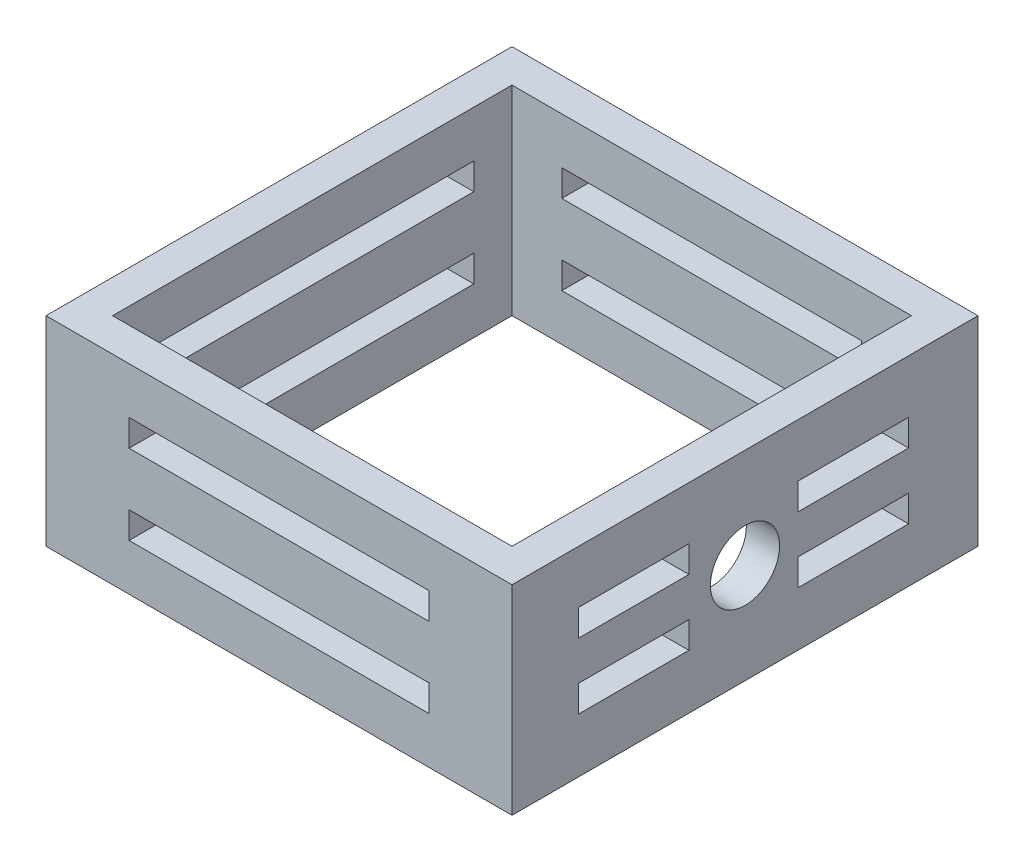
SolidWorks part; units mm, degrees
ref_plane "Front Plane" through (0, 0, 0) normal (0, 0, 1) x (1, 0, 0)
ref_plane "Top Plane" through (0, 0, 0) normal (0, 1, 0) x (1, 0, 0)
ref_plane "Right Plane" through (0, 0, 0) normal (1, 0, 0) x (0, 0, -1)
sketch "Sketch2" plane through (0, 0, 0) normal (0, 1, 0) x (1, 0, 0)
  line L1 (-17.5, 17.5) -> (17.5, 17.5)
  line L2 (-17.5, 17.5) -> (-17.5, -17.5)
  line L3 (-17.5, -17.5) -> (17.5, -17.5)
  line L4 (17.5, 17.5) -> (17.5, -17.5)
  line L5 (-17.5, 17.5) -> (17.5, -17.5) construction
  line L6 (-17.5, -17.5) -> (17.5, 17.5) construction
  point P0 (0, 0)
  dimension "D1" = 35
  dimension "D2" = 35
extrude "Boss-Extrude1" add sketch "Sketch2" along normal blind 10 contours L2 L1 L4 L3
sketch "Sketch3" plane through (0, 10, 0) normal (0, 1, 0) x (1, 0, 0)
  line L1 (-17.5, 17.5) -> (17.5, 17.5)
  line L2 (-17.5, 17.5) -> (-17.5, -17.5)
  line L3 (-17.5, -17.5) -> (17.5, -17.5)
  line L4 (17.5, 17.5) -> (17.5, -17.5)
  line L5 (-17.5, 17.5) -> (17.5, -17.5) construction
  line L6 (-17.5, -17.5) -> (17.5, 17.5) construction
  line L7 (-15, 15) -> (15, 15)
  line L8 (-15, 15) -> (-15, -15)
  line L9 (-15, -15) -> (15, -15)
  line L10 (15, 15) -> (15, -15)
  line L11 (-15, 15) -> (15, -15) construction
  line L12 (-15, -15) -> (15, 15) construction
  point P0 (0, 0)
  point P7 (0, 0)
  dimension "D1" = 30
extrude "Boss-Extrude2" add sketch "Sketch3" along normal blind 15 separate body
sketch "Sketch4" plane through (0, 25, 0) normal (0, 1, 0) x (1, 0, 0)
  line L1 (-17.5, 17.5) -> (17.5, 17.5)
  line L2 (-17.5, 17.5) -> (-17.5, -17.5)
  line L3 (-17.5, -17.5) -> (17.5, -17.5)
  line L4 (17.5, 17.5) -> (17.5, -17.5)
  line L5 (-17.5, 17.5) -> (17.5, -17.5) construction
  line L6 (-17.5, -17.5) -> (17.5, 17.5) construction
  point P0 (0, 0)
extrude "Boss-Extrude3" add sketch "Sketch4" along normal blind 15 separate body
sketch "Sketch5" plane through (0, 40, 0) normal (0, 1, 0) x (1, 0, 0)
  circle A0 centre (0, 0) radius 3.05
extrude "Cut-Extrude1" cut sketch "Sketch5" against normal up to surface (40 mm away)
delete or keep bodies "Body-Delete/Keep 2" type delete bodies bodies 104 105
sketch "Sketch6" plane through (17.5, 0, 0) normal (1, 0, 0) x (0, 0, -1)
  line L0 (-17.5, 17.5) -> (17.5, 17.5) construction
  line L1 (-17.5, 25) -> (-17.5, 10) construction
  line L2 (17.5, 25) -> (17.5, 10) construction
  line L3 (3.9909, 19) -> (3.9909, 16) construction
  line L4 (3.5, 21) -> (-3.5, 21)
  line L5 (3.5, 21) -> (3.5, 14)
  line L6 (3.5, 14) -> (-3.5, 14)
  line L7 (-3.5, 21) -> (-3.5, 14)
  line L8 (3.5, 21) -> (-3.5, 14) construction
  line L9 (3.5, 14) -> (-3.5, 21) construction
  line L10 (3.9909, 14.0645) -> (3.9909, 16.0645)
  line L11 (3.9909, 19) -> (12.287, 19)
  line L12 (3.9909, 19) -> (3.9909, 21)
  line L13 (3.9909, 21) -> (12.287, 21)
  line L14 (12.287, 19) -> (12.287, 21)
  line L15 (3.9909, 14.0645) -> (12.287, 14.0645)
  line L16 (12.287, 14.0645) -> (12.287, 16.0645)
  line L17 (3.9909, 16.0645) -> (12.287, 16.0645)
  line L18 (-12.5091, 14.09) -> (-12.5091, 16.09)
  line L19 (-12.5091, 14.09) -> (-4.213, 14.09)
  line L20 (-4.213, 14.09) -> (-4.213, 16.09)
  line L21 (-12.5091, 16.09) -> (-4.213, 16.09)
  line L22 (-12.5091, 19.0255) -> (-12.5091, 21.0255)
  line L23 (-12.5091, 19.0255) -> (-4.213, 19.0255)
  line L24 (-4.213, 19.0255) -> (-4.213, 21.0255)
  line L25 (-12.5091, 21.0255) -> (-4.213, 21.0255)
  circle A0 centre (0, 17.5) radius 2.6
  point P15 (3.9909, 17.5)
  dimension "D1" = 3
  dimension "D2" = 90
  dimension "D3" = 2
  dimension "D4" = 2
extrude "Cut-Extrude2" cut sketch "Sketch6" against normal up to surface (2.5 mm away) contours A0 | L22 L25 L24 L23 | L12 L11 L14 L13 | L10 L17 L16 L15 | L18 L21 L20 L19 up to face at (15, 17.5, 0)
sketch "Sketch7" plane through (0, 0, 17.5) normal (0, 0, 1) x (1, 0, 0)
  line L0 (17.5, 17.5) -> (-17.5, 17.5) construction
  line L1 (17.5, 25) -> (17.5, 10) construction
  line L2 (-17.5, 25) -> (-17.5, 10) construction
  line L3 (0, 14.5) -> (0, 20.5) construction
  line L8 (-11.2591, 15.5) -> (11.2591, 19.5) construction
  line L9 (-11.2591, 19.5) -> (11.1079, 15.5269) construction
  line L15 (-11.2591, 21.5) -> (11.2591, 21.5)
  line L16 (-11.2591, 21.5) -> (-11.2591, 19.5)
  line L17 (-11.2591, 19.5) -> (11.2591, 19.5)
  line L18 (11.2591, 21.5) -> (11.2591, 19.5)
  line L19 (-11.2591, 21.5) -> (11.2591, 19.5) construction
  line L20 (-11.2591, 19.5) -> (11.2591, 21.5) construction
  line L21 (-11.2591, 13.5) -> (11.2591, 13.5)
  line L22 (-11.2591, 13.5) -> (-11.2591, 15.5)
  line L23 (-11.2591, 15.5) -> (11.2591, 15.5)
  line L24 (11.2591, 13.5) -> (11.2591, 15.5)
  line L25 (-11.2591, 13.5) -> (11.2591, 15.5) construction
  line L26 (-11.2591, 15.5) -> (11.2591, 13.5) construction
  point P6 (0, 17.5)
  point P15 (0, 17.5)
  dimension "D1" = 2
  dimension "D2" = 6
extrude "Cut-Extrude3" cut sketch "Sketch7" against normal up to surface (35 mm away) up to face at (0, 17.5, -17.5)
sketch "Sketch8" plane through (-17.5, 0, 0) normal (-1, 0, 0) x (0, 0, 1)
  line L0 (-17.5, 17.5) -> (17.5, 17.5) construction
  line L1 (-17.5, 25) -> (-17.5, 10) construction
  line L2 (17.5, 25) -> (17.5, 10) construction
  line L3 (0, 20.5) -> (0, 14.5) construction
  line L5 (12.1303, 21.5) -> (-12.1303, 21.5)
  line L6 (12.1303, 21.5) -> (12.1303, 19.5)
  line L7 (12.1303, 19.5) -> (-12.1303, 19.5)
  line L8 (-12.1303, 21.5) -> (-12.1303, 19.5)
  line L9 (12.1303, 21.5) -> (-12.1303, 19.5) construction
  line L10 (12.1303, 19.5) -> (-12.1303, 21.5) construction
  line L11 (12.1303, 13.5) -> (-12.1303, 13.5)
  line L12 (12.1303, 13.5) -> (12.1303, 15.5)
  line L13 (12.1303, 15.5) -> (-12.1303, 15.5)
  line L14 (-12.1303, 13.5) -> (-12.1303, 15.5)
  line L15 (12.1303, 13.5) -> (-12.1303, 15.5) construction
  line L16 (12.1303, 15.5) -> (-12.1303, 13.5) construction
  point P10 (0, 17.5)
  dimension "D1" = 6
  dimension "D2" = 2
  dimension "D3" = 2
extrude "Cut-Extrude4" cut sketch "Sketch8" against normal up to surface (2.5 mm away) up to face at (-15, 17.5, 0)
